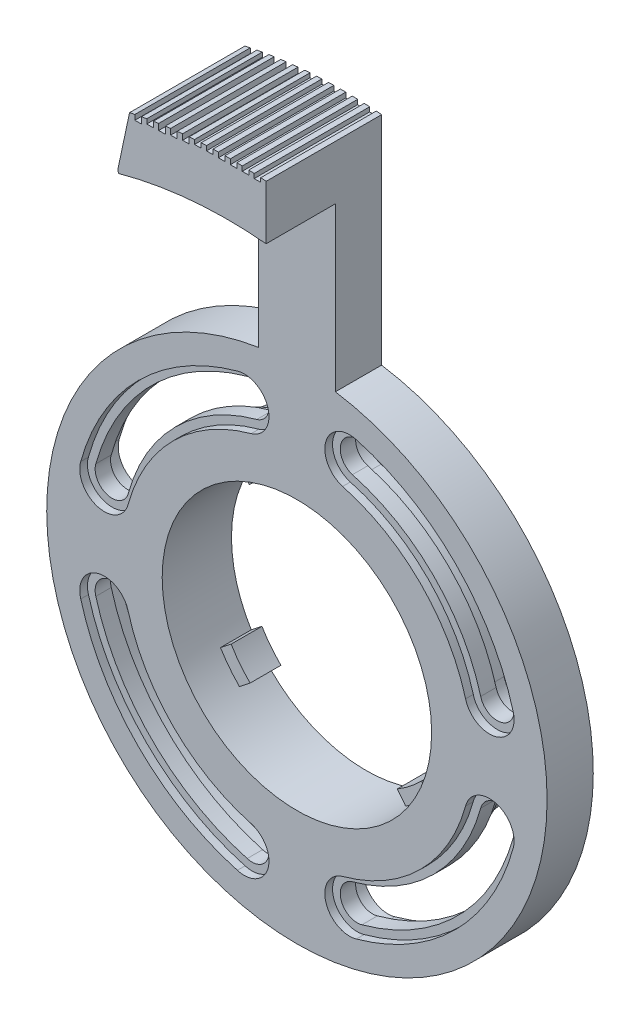
SolidWorks part; units mm, degrees
ref_plane "Front Plane" through (0, 0, 0) normal (0, 0, 1) x (1, 0, 0)
ref_plane "Top Plane" through (0, 0, 0) normal (0, 1, 0) x (1, 0, 0)
ref_plane "Right Plane" through (0, 0, 0) normal (1, 0, 0) x (0, 0, -1)
sketch "Sketch1" plane through (0, 0, 0) normal (0, 0, 1) x (1, 0, 0)
  circle A0 centre (0, 0) radius 32.5
  dimension "D1" = 65
extrude "Boss-Extrude1" add sketch "Sketch1" along normal blind 5
sketch "Sketch3" plane through (0, 0, 0) normal (0, 0, -1) x (-1, 0, 0)
  line L0 (0, 0) -> (0, 63.4996) construction
  line L1 (5, 32.1131) -> (5, 63.4996)
  line L2 (-5, 32.1131) -> (-5, 63.4996)
  line L3 (-5, 63.4996) -> (5, 63.4996)
  line L4 (5, 0) -> (5, 63.4996) construction
  line L5 (-5, 0) -> (-5, 63.4996) construction
  arc A0 (5, 32.1131) -> (-5, 32.1131) centre (0, 0) ccw
  dimension "D1" = 5
  dimension "D2" = 5
extrude "Boss-Extrude3" add sketch "Sketch3" against normal blind 5
sketch "Sketch4" plane through (0, 0, 0) normal (0, 0, -1) x (-1, 0, 0)
  circle A0 centre (0, 0) radius 17.5
  dimension "D1" = 35
extrude "Cut-Extrude1" cut sketch "Sketch4" against normal blind 5
sketch "Sketch5" plane through (0, 0, 0) normal (0, 0, -1) x (-1, 0, 0)
  circle A0 centre (0, 0) radius 17.5 construction
  circle A1 centre (0, 0) radius 17.5
  circle A2 centre (0, 0) radius 21.5
  dimension "D1" = 4
extrude "Boss-Extrude4" add sketch "Sketch5" along normal blind 4
sketch "Sketch7" plane through (0, 0, 0) normal (0, 0, -1) x (-1, 0, 0)
  circle A0 centre (0, 0) radius 30.5
  arc A1 (-5, 32.1131) -> (5, 32.1131) centre (0, 0) ccw construction
  circle A2 centre (0, 0) radius 32.5
  dimension "D1" = 2
extrude "Boss-Extrude5" add sketch "Sketch7" along normal blind 1
sketch "Sketch8" plane through (0, 0, 0) normal (0, 0, -1) x (-1, 0, 0)
  line L0 (0, 68.068) -> (0, -44.6921) construction
  line L1 (-50.9328, 0) -> (55.1912, 0) construction
  line L2 (-40.6445, 40.6445) -> (0, 0) construction
  line L3 (0, 0) -> (42.7877, -42.7877) construction
  line L4 (-34.0461, -34.0461) -> (0, 0) construction
  line L5 (0, 0) -> (37.823, 37.823) construction
  line L6 (0, 0) -> (-11.7639, 42.7378) construction
  line L7 (0, 0) -> (-52.3896, 14.4207) construction
  arc A1 (-7.7294, 28.0805) -> (-6.0311, 21.9109) centre (-6.8282, 25.01) cw
  arc A2 (-28.0805, 7.7294) -> (-21.9109, 6.0311) centre (-25.01, 6.8282) ccw
  arc A3 (-21.9109, 6.0311) -> (-5.9398, 21.9358) centre (0, 0) cw
  arc A4 (-28.0805, 7.7294) -> (-7.7294, 28.0805) centre (0, 0) cw
  arc A5 (28.0805, 7.7294) -> (21.9109, 6.0311) centre (25.01, 6.8282) cw
  arc A6 (28.0805, 7.7294) -> (7.7294, 28.0805) centre (0, 0) ccw
  arc A7 (7.7294, 28.0805) -> (6.0311, 21.9109) centre (6.8282, 25.01) ccw
  arc A8 (21.9109, 6.0311) -> (5.9398, 21.9358) centre (0, 0) ccw
  arc A9 (28.0805, -7.7294) -> (21.9109, -6.0311) centre (25.01, -6.8282) ccw
  arc A10 (21.9109, -6.0311) -> (5.9398, -21.9358) centre (0, 0) cw
  arc A11 (28.0805, -7.7294) -> (7.7294, -28.0805) centre (0, 0) cw
  arc A12 (7.7294, -28.0805) -> (6.0311, -21.9109) centre (6.8282, -25.01) cw
  arc A13 (-28.0805, -7.7294) -> (-21.9109, -6.0311) centre (-25.01, -6.8282) cw
  arc A14 (-28.0805, -7.7294) -> (-7.7294, -28.0805) centre (0, 0) ccw
  arc A15 (-7.7294, -28.0805) -> (-6.0311, -21.9109) centre (-6.8282, -25.01) ccw
  arc A16 (-21.9109, -6.0311) -> (-5.9398, -21.9358) centre (0, 0) ccw
  dimension "D5" = 3.2
  dimension "D1" = 45
  dimension "D2" = 45
  dimension "D3" = 59.22
  dimension "D4" = 29.61
extrude "Cut-Extrude2" cut sketch "Sketch8" against normal blind 2 contours A4 A2 A3 A1 | A16 A13 A14 A15 | A12 A11 A9 A10 | A8 A5 A6 A7
sketch "Sketch9" plane through (0, 0, 2) normal (0, 0, -1) x (-1, 0, 0)
  arc A12 (22.8775, 6.2875) -> (6.2101, 22.8986) centre (0, 0) ccw
  arc A13 (22.8775, 6.2875) -> (27.1188, 7.4552) centre (25.01, 6.8282) ccw
  arc A14 (27.1188, 7.4552) -> (7.4552, 27.1188) centre (0, 0) ccw
  arc A15 (7.4552, 27.1188) -> (6.2101, 22.8986) centre (6.8282, 25.01) ccw
  arc A16 (22.8775, 6.2875) -> (6.2101, 22.8986) centre (0, 0) ccw
  arc A17 (22.8775, 6.2875) -> (27.1188, 7.4552) centre (25.01, 6.8282) ccw
  arc A18 (27.1188, 7.4552) -> (7.4552, 27.1188) centre (0, 0) ccw
  arc A19 (7.4552, 27.1188) -> (6.2101, 22.8986) centre (6.8282, 25.01) ccw
  arc A24 (6.2101, -22.8986) -> (7.4552, -27.1188) centre (6.8282, -25.01) ccw
  arc A25 (7.4552, -27.1188) -> (27.1188, -7.4552) centre (0, 0) ccw
  arc A26 (27.1188, -7.4552) -> (22.8775, -6.2875) centre (25.01, -6.8282) ccw
  arc A27 (6.2101, -22.8986) -> (22.8775, -6.2875) centre (0, 0) ccw
  arc A28 (6.2101, -22.8986) -> (7.4552, -27.1188) centre (6.8282, -25.01) ccw
  arc A29 (7.4552, -27.1188) -> (27.1188, -7.4552) centre (0, 0) ccw
  arc A30 (27.1188, -7.4552) -> (22.8775, -6.2875) centre (25.01, -6.8282) ccw
  arc A31 (6.2101, -22.8986) -> (22.8775, -6.2875) centre (0, 0) ccw
  arc A36 (-22.8775, -6.2875) -> (-6.2101, -22.8986) centre (0, 0) ccw
  arc A37 (-22.8775, -6.2875) -> (-27.1188, -7.4552) centre (-25.01, -6.8282) ccw
  arc A38 (-27.1188, -7.4552) -> (-7.4552, -27.1188) centre (0, 0) ccw
  arc A39 (-7.4552, -27.1188) -> (-6.2101, -22.8986) centre (-6.8282, -25.01) ccw
  arc A40 (-22.8775, -6.2875) -> (-6.2101, -22.8986) centre (0, 0) ccw
  arc A41 (-22.8775, -6.2875) -> (-27.1188, -7.4552) centre (-25.01, -6.8282) ccw
  arc A42 (-27.1188, -7.4552) -> (-7.4552, -27.1188) centre (0, 0) ccw
  arc A43 (-7.4552, -27.1188) -> (-6.2101, -22.8986) centre (-6.8282, -25.01) ccw
  arc A48 (-7.4552, 27.1188) -> (-27.1188, 7.4552) centre (0, 0) ccw
  arc A49 (-27.1188, 7.4552) -> (-22.8775, 6.2875) centre (-25.01, 6.8282) ccw
  arc A50 (-6.2101, 22.8986) -> (-22.8775, 6.2875) centre (0, 0) ccw
  arc A51 (-6.2101, 22.8986) -> (-7.4552, 27.1188) centre (-6.8282, 25.01) ccw
  arc A52 (-7.4552, 27.1188) -> (-27.1188, 7.4552) centre (0, 0) ccw
  arc A53 (-27.1188, 7.4552) -> (-22.8775, 6.2875) centre (-25.01, 6.8282) ccw
  arc A54 (-6.2101, 22.8986) -> (-22.8775, 6.2875) centre (0, 0) ccw
  arc A55 (-6.2101, 22.8986) -> (-7.4552, 27.1188) centre (-6.8282, 25.01) ccw
  dimension "D1" = 1
  dimension "D2" = 1
  dimension "D3" = 1
  dimension "D4" = 1
extrude "Cut-Extrude3" cut sketch "Sketch9" against normal blind 3
sketch "Sketch11" plane through (0, 0, 5) normal (0, 0, 1) x (1, 0, 0)
  line L0 (-5, 53.2658) -> (-5, 60.293)
  line L2 (5, 53.2658) -> (5, 60.293)
  arc A0 (-5, 53.2658) -> (5, 53.2658) centre (0, 0) cw
  arc A1 (-5, 60.293) -> (5, 60.293) centre (0, 0) cw
  dimension "D1" = 53.5
  dimension "D2" = 7
extrude "Boss-Extrude6" add sketch "Sketch11" along normal blind 9
sketch "Sketch12" plane through (0, 0, 5) normal (0, 0, 1) x (1, 0, 0)
  line L0 (5, 53.2658) -> (5, 60.293) construction
  line L1 (-5, 60.293) -> (-5, 63.4996)
  line L2 (-5, 63.4996) -> (5, 63.4996)
  line L3 (5, 63.4996) -> (5, 60.293)
  arc A0 (-5, 60.293) -> (5, 60.293) centre (0, 0) cw
extrude "Cut-Extrude4" cut sketch "Sketch12" against normal blind 5
sketch "Sketch14" plane through (0, 0, 0) normal (0, 0, -1) x (-1, 0, 0)
  line L4 (5, 32.1131) -> (5, 60.293)
  line L5 (-5, 60.293) -> (-5, 32.1131)
  line L6 (5, 32.1131) -> (5, 60.293)
  line L7 (-5, 60.293) -> (-5, 32.1131)
  arc A4 (5, 60.293) -> (-5, 60.293) centre (0, 0) ccw
  arc A5 (5, 32.1131) -> (-5, 32.1131) centre (0, 0) ccw
  arc A6 (5, 60.293) -> (-5, 60.293) centre (0, 0) ccw
  arc A7 (5, 32.1131) -> (-5, 32.1131) centre (0, 0) ccw
  dimension "D1" = 0
extrude "Boss-Extrude7" add sketch "Sketch14" along normal blind 1
sketch "Sketch15" plane through (0, 0, -1) normal (0, 0, -1) x (-1, 0, 0)
  line L2 (0, 60.5) -> (0, 44.5482) construction
  line L3 (5, 60.293) -> (5, 53.2658)
  line L4 (14.3554, 51.5381) -> (16.2337, 58.2814)
  arc A2 (5, 60.293) -> (-5, 60.293) centre (0, 0) ccw construction
  arc A3 (5, 53.2658) -> (14.3554, 51.5381) centre (0, 0) cw
  arc A4 (5, 60.293) -> (16.2337, 58.2814) centre (0, 0) cw
extrude "Boss-Extrude8" add sketch "Sketch15" against normal blind 15
sketch "Sketch16" plane through (0, 0, 14) normal (0, 0, 1) x (1, 0, 0)
  line L0 (-14.3554, 51.5381) -> (-12.7441, 59.1425)
  line L1 (-14.3554, 51.5381) -> (-16.2337, 58.2814) construction
  line L2 (-14.3554, 51.5381) -> (-16.2337, 58.2814)
  arc A0 (5, 60.293) -> (-16.2337, 58.2814) centre (0, 0) ccw construction
  arc A1 (-12.7441, 59.1425) -> (-16.2337, 58.2814) centre (0, 0) ccw
extrude "Cut-Extrude5" cut sketch "Sketch16" against normal blind 15
sketch "Sketch18" plane through (0, 0, -1) normal (0, 0, -1) x (-1, 0, 0)
  line L0 (-5, 60.293) -> (-5, 32.1131) construction
  line L1 (-4.3, 60.5213) -> (-3.45, 60.5213)
  line L2 (-4.3, 60.5213) -> (-4.3, 59.8223)
  line L3 (-4.3, 59.8223) -> (-3.45, 59.8223)
  line L4 (-3.45, 60.5213) -> (-3.45, 59.8223)
  line L5 (-2.75, 60.6462) -> (-1.9, 60.6462)
  line L6 (-2.75, 60.6462) -> (-2.75, 59.8656)
  line L7 (-2.75, 59.8656) -> (-1.9, 59.8656)
  line L8 (-1.9, 60.6462) -> (-1.9, 59.8656)
  line L9 (-1.2, 60.8289) -> (-0.35, 60.8289)
  line L10 (-1.2, 60.8289) -> (-1.2, 59.8405)
  line L11 (-1.2, 59.8405) -> (-0.35, 59.8405)
  line L12 (-0.35, 60.8289) -> (-0.35, 59.8405)
  line L13 (0.35, 60.8289) -> (1.2, 60.8289)
  line L14 (0.35, 60.8289) -> (0.35, 59.8405)
  line L15 (0.35, 59.8405) -> (1.2, 59.8405)
  line L16 (1.2, 60.8289) -> (1.2, 59.8405)
  line L17 (1.9, 60.8289) -> (2.75, 60.8289)
  line L18 (1.9, 60.8289) -> (1.9, 59.8405)
  line L19 (1.9, 59.8405) -> (2.75, 59.8405)
  line L20 (2.75, 60.8289) -> (2.75, 59.8405)
  line L21 (3.45, 60.6462) -> (4.3, 60.6462)
  line L22 (3.45, 60.6462) -> (3.45, 59.794)
  line L23 (3.45, 59.794) -> (4.3, 59.794)
  line L24 (4.3, 60.6462) -> (4.3, 59.794)
  line L25 (6.55, 60.4332) -> (7.4, 60.4332)
  line L26 (6.55, 60.4332) -> (6.55, 59.2891)
  line L27 (6.55, 59.2891) -> (7.4, 59.2891)
  line L28 (7.4, 60.4332) -> (7.4, 59.2891)
  line L29 (8.1, 60.2201) -> (8.95, 60.2201)
  line L30 (8.1, 60.2201) -> (8.1, 59.0385)
  line L31 (8.1, 59.0385) -> (8.95, 59.0385)
  line L32 (8.95, 60.2201) -> (8.95, 59.0385)
  line L33 (9.65, 60.1411) -> (10.5, 60.1411)
  line L34 (9.65, 60.1411) -> (9.65, 58.9883)
  line L35 (9.65, 58.9883) -> (10.5, 58.9883)
  line L36 (10.5, 60.1411) -> (10.5, 58.9883)
  line L37 (5, 60.8289) -> (5.85, 60.8289)
  line L38 (5, 60.8289) -> (5, 59.4896)
  line L39 (5, 59.4896) -> (5.85, 59.4896)
  line L40 (5.85, 60.8289) -> (5.85, 59.4896)
  line L42 (11.2, 59.963) -> (12.05, 59.963)
  line L43 (11.2, 59.963) -> (11.2, 58.6374)
  line L44 (11.2, 58.6374) -> (12.05, 58.6374)
  line L45 (12.05, 59.963) -> (12.05, 58.6374)
  dimension "D1" = 0.7
  dimension "D2" = 0.7
  dimension "D3" = 0.7
  dimension "D4" = 0.7
  dimension "D5" = 0.7
  dimension "D6" = 0.7
  dimension "D7" = 0.7
  dimension "D8" = 0.7
  dimension "D9" = 0.7
  dimension "D10" = 0.85
  dimension "D11" = 0.85
  dimension "D12" = 0.85
  dimension "D13" = 0.85
  dimension "D14" = 0.85
  dimension "D15" = 0.85
  dimension "D16" = 0.85
  dimension "D17" = 0.85
  dimension "D18" = 0.85
  dimension "D19" = 0.85
  dimension "D20" = 0.7
  dimension "D21" = 0.7
  dimension "D22" = 0.85
extrude "Cut-Extrude6" cut sketch "Sketch18" against normal blind 15
chamfer "Chamfer1" distance 0.5 angle 20 1 edges at (-14.3554, 51.5381, 6.5)
sketch "Sketch19" plane through (0, 0, -4) normal (0, 0, -1) x (-1, 0, 0)
  line L0 (-13.9872, 10.928) -> (13.9872, -10.928) construction
  line L1 (-10.928, -13.9872) -> (10.928, 13.9872) construction
  line L2 (-15.1294, 9.2824) -> (-13.542, 8.0421)
  line L3 (-12.6668, 12.4344) -> (-11.0794, 11.1942)
  line L4 (-9.2824, -15.1294) -> (-8.0421, -13.542)
  line L5 (-12.4344, -12.6668) -> (-11.1942, -11.0794)
  line L6 (8.0421, 13.542) -> (9.2824, 15.1294)
  line L7 (11.1942, 11.0794) -> (12.4344, 12.6668)
  line L15 (11.0794, -11.1942) -> (12.6668, -12.4344)
  line L17 (13.542, -8.0421) -> (15.1294, -9.2824)
  arc A1 (-12.4344, -12.6668) -> (-9.2824, -15.1294) centre (0, 0) ccw
  arc A2 (-11.1942, -11.0794) -> (-8.0421, -13.542) centre (0, 0) ccw
  arc A3 (12.4344, 12.6668) -> (9.2824, 15.1294) centre (0, 0) ccw
  arc A4 (-11.0794, 11.1942) -> (-13.542, 8.0421) centre (0, 0) ccw
  arc A6 (-12.6668, 12.4344) -> (-15.1294, 9.2824) centre (0, 0) ccw
  arc A7 (11.1942, 11.0794) -> (8.0421, 13.542) centre (0, 0) ccw
  arc A8 (12.4344, 12.6668) -> (9.2824, 15.1294) centre (0, 0) ccw
  arc A9 (11.0794, -11.1942) -> (13.542, -8.0421) centre (0, 0) ccw
  arc A11 (12.6668, -12.4344) -> (15.1294, -9.2824) centre (0, 0) ccw
  arc A12 (-12.4344, -12.6668) -> (-9.2824, -15.1294) centre (0, 0) ccw
  arc A13 (-12.6668, 12.4344) -> (-15.1294, 9.2824) centre (0, 0) ccw
  arc A14 (12.6668, -12.4344) -> (15.1294, -9.2824) centre (0, 0) ccw
  point P7 (0, 0)
  point P10 (-2, 17.75)
  point P11 (-2, -17.75)
  point P12 (2, 17.75)
  point P13 (2, -17.75)
  point P14 (-17.75, -2)
  point P15 (17.75, -2)
  point P16 (-17.75, 2)
  point P17 (17.75, 2)
  point P19 (0, 0)
  point P21 (15.0618, 4.6049)
  point P33 (17.75, 0)
  circle M7 centre (0, 0) radius 17.5
  dimension "D5" = 2
extrude "Boss-Extrude10" add sketch "Sketch19" against normal blind 4 contours A4 L3 L2 M7 | A7 L7 L6 M7 | A9 L15 L17 M7 | A2 L5 L4 M7
sketch "Sketch20" plane through (0, 0, 5) normal (0, 0, 1) x (1, 0, 0)
  arc A11 (-28.0805, 7.7294) -> (-21.9109, 6.0311) centre (-25.01, 6.8282) ccw
  arc A12 (-7.7294, 28.0805) -> (-28.0805, 7.7294) centre (0, 0) ccw
  arc A13 (-5.9398, 21.9358) -> (-7.7294, 28.0805) centre (-6.8282, 25.01) ccw
  arc A14 (-5.9398, 21.9358) -> (-21.9109, 6.0311) centre (0, 0) ccw
  arc A15 (-28.0805, 7.7294) -> (-21.9109, 6.0311) centre (-25.01, 6.8282) ccw
  arc A16 (-7.7294, 28.0805) -> (-28.0805, 7.7294) centre (0, 0) ccw
  arc A17 (-5.9398, 21.9358) -> (-7.7294, 28.0805) centre (-6.8282, 25.01) ccw
  arc A18 (5.9398, -21.9358) -> (7.7294, -28.0805) centre (6.8282, -25.01) ccw
  arc A19 (7.7294, -28.0805) -> (28.0805, -7.7294) centre (0, 0) ccw
  arc A20 (28.0805, -7.7294) -> (21.9109, -6.0311) centre (25.01, -6.8282) ccw
  arc A21 (5.9398, -21.9358) -> (21.9109, -6.0311) centre (0, 0) ccw
  arc A22 (5.9398, -21.9358) -> (7.7294, -28.0805) centre (6.8282, -25.01) ccw
  arc A23 (7.7294, -28.0805) -> (28.0805, -7.7294) centre (0, 0) ccw
  arc A24 (28.0805, -7.7294) -> (21.9109, -6.0311) centre (25.01, -6.8282) ccw
  arc A25 (5.9398, -21.9358) -> (21.9109, -6.0311) centre (0, 0) ccw
  arc A26 (-5.9398, 21.9358) -> (-21.9109, 6.0311) centre (0, 0) ccw
  arc A37 (21.9109, 6.0311) -> (28.0805, 7.7294) centre (25.01, 6.8282) ccw
  arc A38 (28.0805, 7.7294) -> (7.7294, 28.0805) centre (0, 0) ccw
  arc A39 (21.9109, 6.0311) -> (5.9398, 21.9358) centre (0, 0) ccw
  arc A40 (7.7294, 28.0805) -> (5.9398, 21.9358) centre (6.8282, 25.01) ccw
  arc A41 (21.9109, 6.0311) -> (28.0805, 7.7294) centre (25.01, 6.8282) ccw
  arc A42 (28.0805, 7.7294) -> (7.7294, 28.0805) centre (0, 0) ccw
  arc A43 (21.9109, 6.0311) -> (5.9398, 21.9358) centre (0, 0) ccw
  arc A44 (7.7294, 28.0805) -> (5.9398, 21.9358) centre (6.8282, 25.01) ccw
  arc A87 (-7.7294, -28.0805) -> (-5.9398, -21.9358) centre (-6.8282, -25.01) ccw
  arc A88 (-21.9109, -6.0311) -> (-5.9398, -21.9358) centre (0, 0) ccw
  arc A89 (-28.0805, -7.7294) -> (-7.7294, -28.0805) centre (0, 0) ccw
  arc A90 (-21.9109, -6.0311) -> (-28.0805, -7.7294) centre (-25.01, -6.8282) ccw
  arc A91 (-7.7294, -28.0805) -> (-5.9398, -21.9358) centre (-6.8282, -25.01) ccw
  arc A92 (-21.9109, -6.0311) -> (-5.9398, -21.9358) centre (0, 0) ccw
  arc A93 (-28.0805, -7.7294) -> (-7.7294, -28.0805) centre (0, 0) ccw
  arc A94 (-21.9109, -6.0311) -> (-28.0805, -7.7294) centre (-25.01, -6.8282) ccw
  dimension "D1" = 1
  dimension "D2" = 1
  dimension "D3" = 1
  dimension "D4" = 1
extrude "Cut-Extrude7" cut sketch "Sketch20" against normal blind 1
